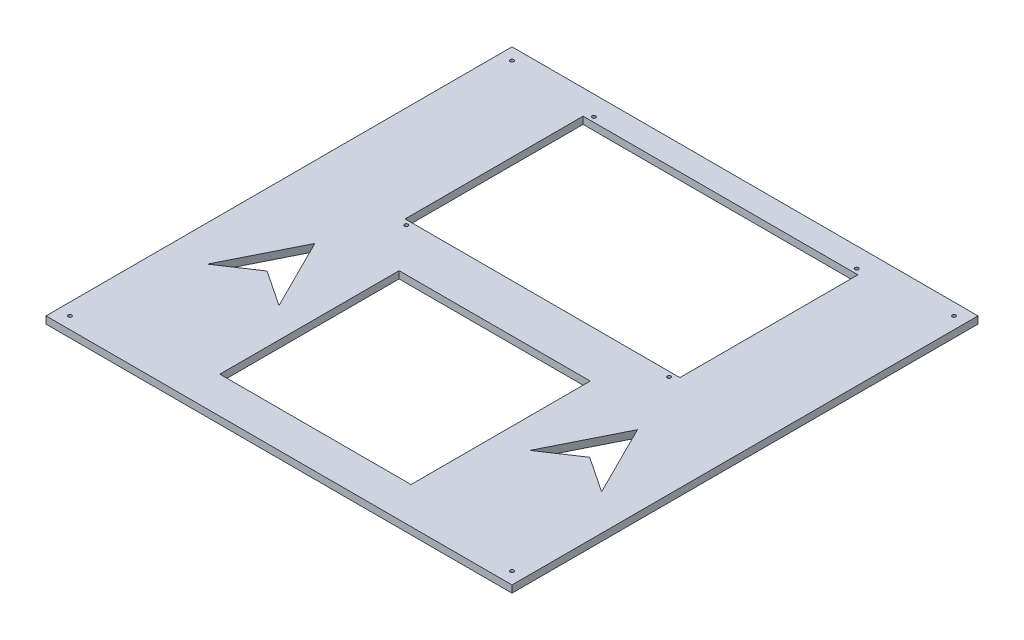
SolidWorks part; units mm, degrees
ref_plane "前视基准面" through (0, 0, 0) normal (0, 0, 1) x (1, 0, 0)
ref_plane "上视基准面" through (0, 0, 0) normal (0, 1, 0) x (1, 0, 0)
ref_plane "右视基准面" through (0, 0, 0) normal (1, 0, 0) x (0, 0, -1)
other "Configuration Table"
sketch "草图2" plane through (0, 0, 0) normal (0, 1, 0) x (1, 0, 0)
  line L0 (195, -195) -> (195, 195)
  line L1 (195, 195) -> (-195, 195)
  line L2 (-195, 195) -> (-195, -195)
  line L3 (-195, -195) -> (195, -195)
  line L4 (115, 174.5) -> (-115, 174.5)
  line L5 (115, 25.5) -> (115, 174.5)
  line L6 (-115, 25.5) -> (115, 25.5)
  line L7 (-115, 174.5) -> (-115, 25.5)
  line L8 (80, -14.5) -> (-80, -14.5)
  line L9 (80, -14.5) -> (80, -164.5)
  line L10 (-80, -164.5) -> (80, -164.5)
  line L11 (-80, -14.5) -> (-80, -164.5)
  line L12 (-135, -70) -> (-105, -90)
  line L13 (-165, -90) -> (-135, -70)
  line L14 (-135, -30) -> (-165, -90)
  line L15 (-105, -90) -> (-135, -30)
  line L16 (135, -70) -> (165, -90)
  line L17 (105, -90) -> (135, -70)
  line L18 (135, -30) -> (105, -90)
  line L19 (165, -90) -> (135, -30)
  line L20 (0, -210.1089) -> (0, 239.7569) construction
  line L21 (-115, 174.5) -> (115, 25.5) construction
  line L22 (-115, 25.5) -> (115, 174.5) construction
  circle A0 centre (185, -185) radius 1.5
  circle A1 centre (-185, 185) radius 1.5
  circle A2 centre (110, 21.5) radius 1.5
  circle A3 centre (-110, 178.5) radius 1.5
  circle A6 centre (-110, 21.5) radius 1.5
  circle A7 centre (110, 178.5) radius 1.5
  circle A8 centre (-185, -185) radius 1.5
  circle A9 centre (185, 185) radius 1.5
  point P2 (80, -164.5)
  point P19 (80, -162.2395)
  point P44 (0, -14.5)
  point P45 (0, -164.5)
  dimension "D1" = 160
  dimension "D2" = 390
  dimension "D3" = 390
  dimension "D4" = 195
  dimension "D5" = 195
  dimension "D6" = 150
  dimension "D7" = 40
  dimension "D8" = 20.5
  dimension "D9" = 230
  dimension "D10" = 149
extrude "凸台-拉伸1" add sketch "草图2" along normal blind 6
